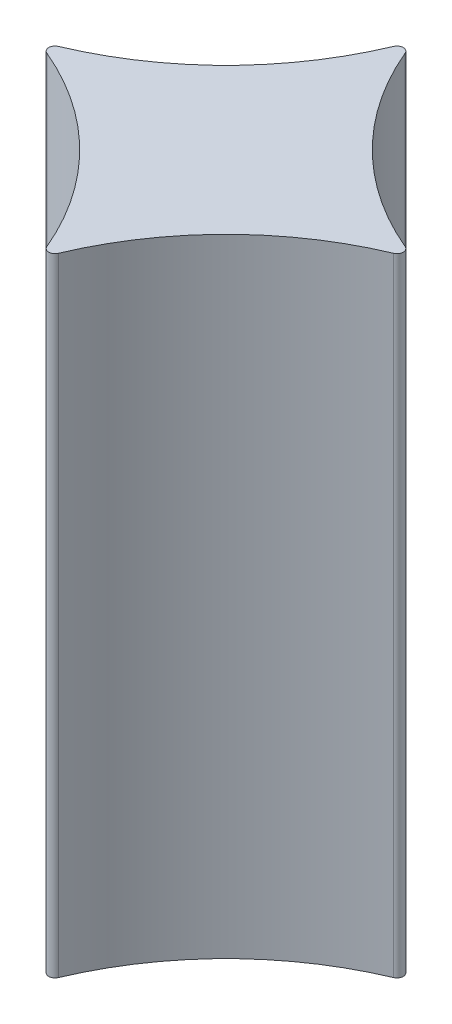
SolidWorks part; units mm, degrees
ref_plane "Front Plane" through (0, 0, 0) normal (0, 0, 1) x (1, 0, 0)
ref_plane "Top Plane" through (0, 0, 0) normal (0, 1, 0) x (1, 0, 0)
ref_plane "Right Plane" through (0, 0, 0) normal (1, 0, 0) x (0, 0, -1)
sketch "Sketch1" plane through (0, 0, 0) normal (0, 1, 0) x (1, 0, 0)
  line L0 (0, 3.3485) -> (0, -5.6888) construction
  line L1 (-4.6556, 0) -> (6.2241, 0) construction
  arc A0 (-0.0922, 2.7641) -> (-2.7641, 0.0922) centre (-4.7016, 4.7016) cw
  arc A1 (0.0922, 2.7641) -> (2.7641, 0.0922) centre (4.7016, 4.7016) ccw
  arc A2 (-2.7641, -0.0922) -> (-0.0922, -2.7641) centre (-4.7016, -4.7016) cw
  arc A3 (0.0922, -2.7641) -> (2.7641, -0.0922) centre (4.7016, -4.7016) cw
  arc A4 (2.7641, 0.0922) -> (2.7641, -0.0922) centre (2.7254, 0) cw
  arc A5 (-2.7641, 0.0922) -> (-2.7641, -0.0922) centre (-2.7254, 0) ccw
  arc A6 (-0.0922, -2.7641) -> (0.0922, -2.7641) centre (0, -2.7254) ccw
  arc A7 (-0.0922, 2.7641) -> (0.0922, 2.7641) centre (0, 2.7254) cw
  point P13 (0, 0)
  point P14 (0, 0)
  point P15 (0, 0)
  point P16 (0, 0)
  point P17 (0, 0)
  point P20 (3, 0)
  point P23 (-3, 0)
  point P26 (0, -3)
  point P29 (0, 3)
  point P30 (0, 0)
  dimension "D3" = 5
  dimension "D4" = 5
  dimension "D5" = 0.1
  dimension "D1" = 3
  dimension "D2" = 3
extrude "Boss-Extrude1" add sketch "Sketch1" along normal blind 10
